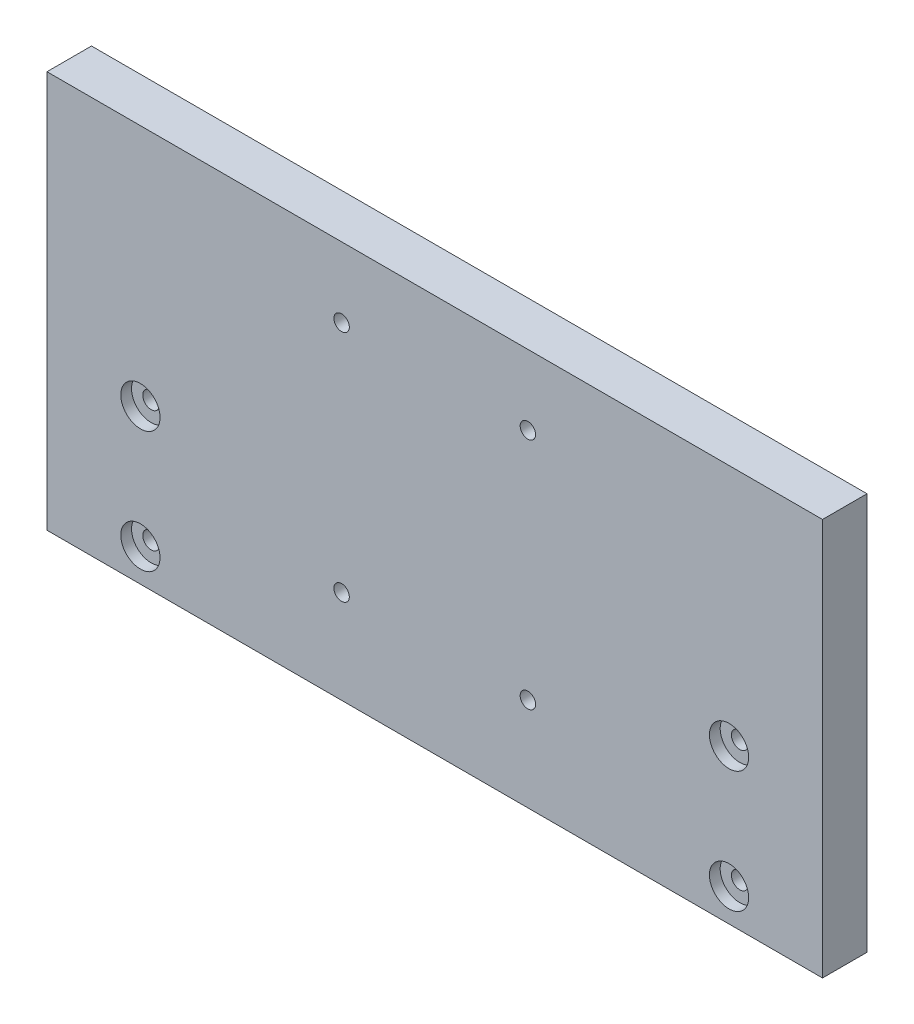
SolidWorks part; units mm, degrees
ref_plane "Front Plane" through (0, 0, 0) normal (0, 0, 1) x (1, 0, 0)
ref_plane "Top Plane" through (0, 0, 0) normal (0, 1, 0) x (1, 0, 0)
ref_plane "Right Plane" through (0, 0, 0) normal (1, 0, 0) x (0, 0, -1)
sketch "Sketch1" plane through (0, 0, 0) normal (0, 0, 1) x (-1, 0, 0)
  line L1 (0, 0) -> (-40, 0)
  line L2 (0, 0) -> (0, -40)
  line L3 (0, -40) -> (-40, -40)
  line L4 (-40, 0) -> (-40, -40)
  line L5 (-126, 0) -> (-166, 0)
  line L6 (-126, 0) -> (-126, -40)
  line L7 (-126, -40) -> (-166, -40)
  line L8 (-166, 0) -> (-166, -40)
  line L9 (0, 0) -> (-166, 0)
  line L10 (0, 0) -> (0, -85)
  line L11 (0, -85) -> (-166, -85)
  line L12 (-166, 0) -> (-166, -85)
  dimension "D5" = 40
  dimension "D6" = 40
  dimension "D16" = 40
  dimension "D17" = 40
  dimension "D21" = 0
  dimension "D22" = 0
  dimension "D23" = 40
  dimension "D24" = 0
  dimension "D33" = 45
extrude "Boss-Extrude3" add sketch "Sketch1" along normal blind 9.53
sketch "Sketch8" plane through (0, 0, 9.53) normal (0, 0, 1) x (1, 0, 0)
  line L0 (0, 0) -> (0, 85) construction
  line L1 (0, 0) -> (166, 0) construction
  line L2 (166, 0) -> (166, 85) construction
  circle A0 centre (20, 33) radius 4.2
  circle A1 centre (20, 7) radius 4.2
  circle A2 centre (146, 7) radius 4.2
  circle A3 centre (146, 33) radius 4.2
  dimension "D1" = 8.4
  dimension "D2" = 8.4
  dimension "D7" = 8.4
  dimension "D12" = 8.4
  dimension "D3" = 20
  dimension "D4" = 20
  dimension "D5" = 26
  dimension "D6" = 7
  dimension "D8" = 26
  dimension "D9" = 20
  dimension "D10" = 7
  dimension "D11" = 20
hole_wizard "CBORE for M3 Hex Head Machine Screw2" positions "3DSketch6" profile "Sketch9" counterbore size "M3" standard "Ansi Metric" end condition through all
sketch3d "3DSketch6"
  point P0 (20, 33, 9.53)
  point P3 (20, 7, 9.53)
  point P6 (146, 33, 9.53)
  point P9 (146, 7, 9.53)
sketch "Sketch9" plane through (20, 33, 9.53) normal (1, 0, 0) x (0, -1, 0)
  line L0 (0, 0) -> (0, 9.53)
  line L1 (0, 9.53) -> (1.8, 9.53)
  line L3 (1.8, 9.53) -> (1.8, 2.3)
  line L4 (1.8, 2.3) -> (4.2, 2.3)
  line L5 (4.2, 2.3) -> (4.2, 0)
  line L7 (4.2, 0) -> (0, 0)
  line L11 (0, -6.35) -> (0, 107.95) construction
  dimension "Thru Hole Dia." = 3.6
  dimension "Thru Hole Depth" = 9.53
  dimension "C'Bore Dia." = 8.4
  dimension "C'Bore Depth" = 2.3
sketch "Sketch10" plane through (0, 0, 9.53) normal (0, 0, 1) x (1, 0, 0)
  line L0 (83, 108.5425) -> (83, 18.5425) construction
  line L1 (0, 0) -> (166, 0) construction
  line L2 (0, 0) -> (0, 85) construction
  circle A0 centre (63.065, 20) radius 2.065
  circle A1 centre (63.065, 70) radius 2.065
  circle A2 centre (102.935, 70) radius 2.065
  circle A3 centre (102.935, 20) radius 2.065
  dimension "D5" = 4.13
  dimension "D6" = 4.13
  dimension "D7" = 4.13
  dimension "D8" = 4.13
  dimension "D1" = 39.87
  dimension "D2" = 39.87
  dimension "D3" = 19.935
  dimension "D4" = 50
  dimension "D9" = 20
  dimension "D10" = 83
hole_wizard "M4x0.7 Tapped Hole1" positions "3DSketch7" profile "Sketch11" tap size "M4x0.7" standard "Ansi Metric"
sketch3d "3DSketch7"
  point P0 (63.065, 70, 9.53)
  point P3 (63.065, 20, 9.53)
  point P6 (102.935, 70, 9.53)
  point P9 (102.935, 20, 9.53)
sketch "Sketch11" plane through (63.065, 70, 9.53) normal (1, 0, 0) x (0, -1, 0)
  line L0 (0, 0) -> (0, 11.0914)
  line L1 (0, 11.0914) -> (1.65, 10.1)
  line L2 (1.65, 10.1) -> (1.65, 0)
  line L5 (1.65, 0) -> (0, 0)
  line L10 (0, 11.0914) -> (-1.65, 10.1) construction
  line L11 (0, -6.35) -> (0, 107.95) construction
  dimension "Tap Drill Dia." = 3.3
  dimension "Tap Drill Depth" = 10.1
  dimension "Drill Angle" = 118
cosmetic thread "Hole Thread1" parameters "D1"=8, "D2"=4
cosmetic thread "Hole Thread2" parameters "D1"=8, "D2"=4
cosmetic thread "Hole Thread3" parameters "D1"=8, "D2"=4
cosmetic thread "Hole Thread4" parameters "D1"=8, "D2"=4
